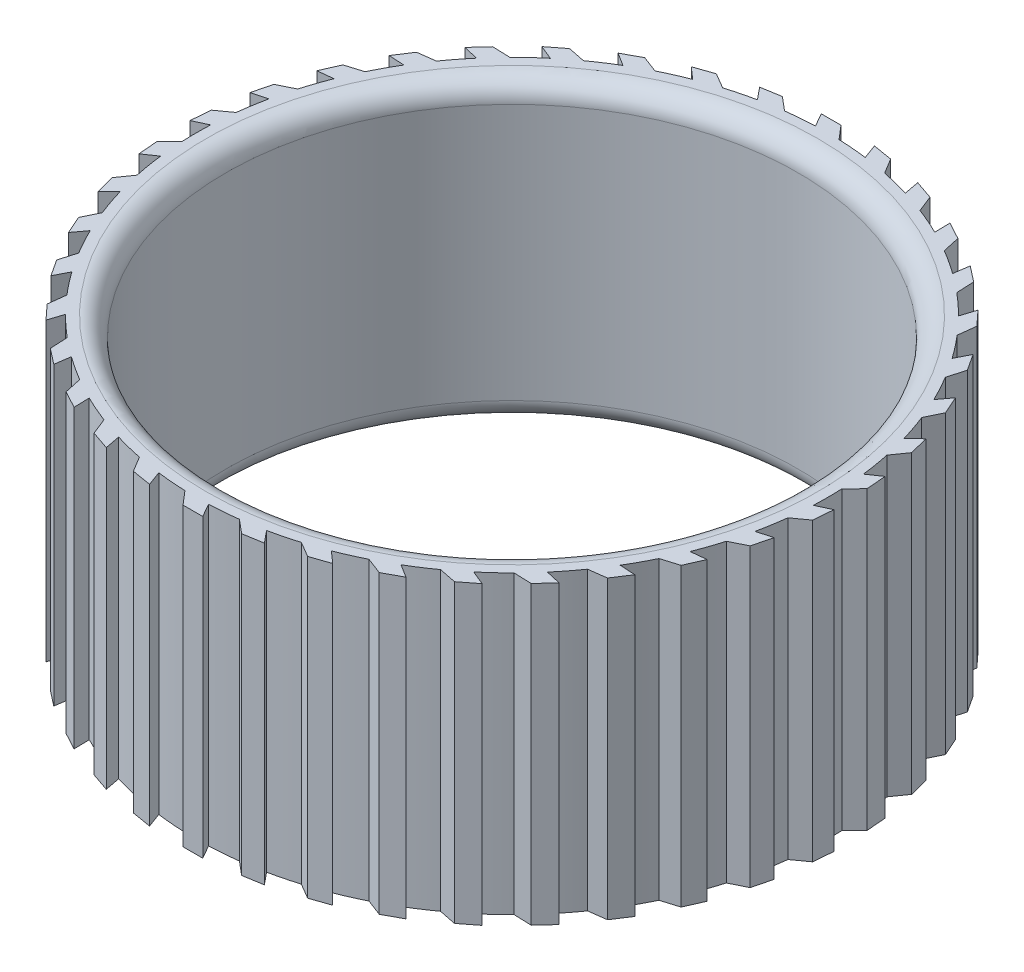
SolidWorks part; units mm, degrees
ref_plane "Front Plane" through (0, 0, 0) normal (0, 0, 1) x (1, 0, 0)
ref_plane "Top Plane" through (0, 0, 0) normal (0, 1, 0) x (1, 0, 0)
ref_plane "Right Plane" through (0, 0, 0) normal (1, 0, 0) x (0, 0, -1)
sketch "Sketch1" plane through (0, 0, 0) normal (0, 1, 0) x (1, 0, 0)
  circle A0 centre (0, 0) radius 29
  circle A1 centre (0, 0) radius 32
  dimension "D1" = 58
  dimension "D2" = 3
extrude "Boss-Extrude1" add sketch "Sketch1" along normal mid plane 30
sketch "Sketch2" plane through (0, -15, 0) normal (0, -1, 0) x (1, 0, 0)
  line L0 (0, -971) -> (0, 49029) construction
  line L1 (0, 33.3457) -> (2, 33.3457)
  line L2 (0, 33.3457) -> (-1.1725, 31.9785)
  line L3 (2, 33.3457) -> (1.2174, 31.9768)
  line L4 (5.4885, 32.8909) -> (4.107, 31.7354)
  line L5 (5.4885, 32.8909) -> (7.4612, 32.5617)
  line L6 (7.4612, 32.5617) -> (6.464, 31.3403)
  line L7 (10.8273, 31.5389) -> (9.2744, 30.6265)
  line L8 (10.8273, 31.5389) -> (12.719, 30.8895)
  line L9 (12.719, 30.8895) -> (11.5343, 29.849)
  line L10 (15.8708, 29.3266) -> (14.1889, 28.6823)
  line L11 (15.8708, 29.3266) -> (17.6297, 28.3747)
  line L12 (17.6297, 28.3747) -> (16.2899, 27.5434)
  line L13 (20.4813, 26.3144) -> (18.7163, 25.9557)
  line L14 (20.4813, 26.3144) -> (22.0596, 25.086)
  line L15 (22.0596, 25.086) -> (20.6012, 24.4865)
  line L16 (24.5332, 22.5844) -> (22.7332, 22.5211)
  line L17 (24.5332, 22.5844) -> (25.8878, 21.1129)
  line L18 (25.8878, 21.1129) -> (24.3506, 20.7617)
  line L19 (27.9159, 18.2383) -> (26.13, 18.4722)
  line L20 (27.9159, 18.2383) -> (29.0098, 16.564)
  line L21 (29.0098, 16.564) -> (27.4358, 16.4705)
  line L22 (30.5371, 13.3948) -> (28.8141, 13.9194)
  line L23 (30.5371, 13.3948) -> (31.3405, 11.5633)
  line L24 (31.3405, 11.5633) -> (29.7725, 11.7301)
  line L25 (32.3253, 8.1859) -> (30.7121, 8.9869)
  line L26 (32.3253, 8.1859) -> (32.8163, 6.2471)
  line L27 (32.8163, 6.2471) -> (31.2972, 6.6697)
  line L28 (33.2318, 2.7537) -> (31.7725, 3.8093)
  line L29 (33.2318, 2.7537) -> (33.3969, 0.7605)
  line L30 (33.3969, 0.7605) -> (31.9681, 1.4274)
  line L31 (33.2318, -2.7537) -> (31.9661, -1.4722)
  line L32 (33.2318, -2.7537) -> (33.0666, -4.7468)
  line L33 (33.0666, -4.7468) -> (31.7671, -3.8538)
  line L34 (32.3253, -8.1859) -> (31.2878, -6.7136)
  line L35 (32.3253, -8.1859) -> (31.8343, -10.1247)
  line L36 (31.8343, -10.1247) -> (30.6995, -9.03)
  line L37 (30.5371, -13.3948) -> (29.7561, -11.7719)
  line L38 (30.5371, -13.3948) -> (29.7337, -15.2263)
  line L39 (29.7337, -15.2263) -> (28.7945, -13.9598)
  line L40 (27.9159, -18.2383) -> (27.4126, -16.509)
  line L41 (27.9159, -18.2383) -> (26.822, -19.9127)
  line L42 (26.822, -19.9127) -> (26.1041, -18.5088)
  line L43 (24.5332, -22.5844) -> (24.3215, -20.7958)
  line L44 (24.5332, -22.5844) -> (23.1786, -24.0558)
  line L45 (23.1786, -24.0558) -> (22.7016, -22.553)
  line L46 (20.4813, -26.3144) -> (20.5669, -24.5154)
  line L47 (20.4813, -26.3144) -> (18.903, -27.5428)
  line L48 (18.903, -27.5428) -> (18.6799, -25.9819)
  line L49 (15.8708, -29.3266) -> (16.2513, -27.5662)
  line L50 (15.8708, -29.3266) -> (14.1118, -30.2785)
  line L51 (14.1118, -30.2785) -> (14.1487, -28.7022)
  line L52 (10.8273, -31.5389) -> (11.4924, -29.8651)
  line L53 (10.8273, -31.5389) -> (8.9357, -32.1883)
  line L54 (8.9357, -32.1883) -> (9.2315, -30.6395)
  line L55 (5.4885, -32.8909) -> (6.42, -31.3494)
  line L56 (5.4885, -32.8909) -> (3.5158, -33.2201)
  line L57 (3.5158, -33.2201) -> (4.0625, -31.7411)
  line L58 (0, -33.3457) -> (1.1725, -31.9785)
  line L59 (0, -33.3457) -> (-2, -33.3457)
  line L60 (-2, -33.3457) -> (-1.2174, -31.9768)
  line L61 (-5.4885, -32.8909) -> (-4.107, -31.7354)
  line L62 (-5.4885, -32.8909) -> (-7.4612, -32.5617)
  line L63 (-7.4612, -32.5617) -> (-6.464, -31.3403)
  line L64 (-10.8273, -31.5389) -> (-9.2744, -30.6265)
  line L65 (-10.8273, -31.5389) -> (-12.719, -30.8895)
  line L66 (-12.719, -30.8895) -> (-11.5343, -29.849)
  line L67 (-15.8708, -29.3266) -> (-14.1889, -28.6823)
  line L68 (-15.8708, -29.3266) -> (-17.6297, -28.3747)
  line L69 (-17.6297, -28.3747) -> (-16.2899, -27.5434)
  line L70 (-20.4813, -26.3144) -> (-18.7163, -25.9557)
  line L71 (-20.4813, -26.3144) -> (-22.0596, -25.086)
  line L72 (-22.0596, -25.086) -> (-20.6012, -24.4865)
  line L73 (-24.5332, -22.5844) -> (-22.7332, -22.5211)
  line L74 (-24.5332, -22.5844) -> (-25.8878, -21.1129)
  line L75 (-25.8878, -21.1129) -> (-24.3506, -20.7617)
  line L76 (-27.9159, -18.2383) -> (-26.13, -18.4722)
  line L77 (-27.9159, -18.2383) -> (-29.0098, -16.564)
  line L78 (-29.0098, -16.564) -> (-27.4358, -16.4705)
  line L79 (-30.5371, -13.3948) -> (-28.8141, -13.9194)
  line L80 (-30.5371, -13.3948) -> (-31.3405, -11.5633)
  line L81 (-31.3405, -11.5633) -> (-29.7725, -11.7301)
  line L82 (-32.3253, -8.1859) -> (-30.7121, -8.9869)
  line L83 (-32.3253, -8.1859) -> (-32.8163, -6.2471)
  line L84 (-32.8163, -6.2471) -> (-31.2972, -6.6697)
  line L85 (-33.2318, -2.7537) -> (-31.7725, -3.8093)
  line L86 (-33.2318, -2.7537) -> (-33.3969, -0.7605)
  line L87 (-33.3969, -0.7605) -> (-31.9681, -1.4274)
  line L88 (-33.2318, 2.7537) -> (-31.9661, 1.4722)
  line L89 (-33.2318, 2.7537) -> (-33.0666, 4.7468)
  line L90 (-33.0666, 4.7468) -> (-31.7671, 3.8538)
  line L91 (-32.3253, 8.1859) -> (-31.2878, 6.7136)
  line L92 (-32.3253, 8.1859) -> (-31.8343, 10.1247)
  line L93 (-31.8343, 10.1247) -> (-30.6995, 9.03)
  line L94 (-30.5371, 13.3948) -> (-29.7561, 11.7719)
  line L95 (-30.5371, 13.3948) -> (-29.7337, 15.2263)
  line L96 (-29.7337, 15.2263) -> (-28.7945, 13.9598)
  line L97 (-27.9159, 18.2383) -> (-27.4126, 16.509)
  line L98 (-27.9159, 18.2383) -> (-26.822, 19.9127)
  line L99 (-26.822, 19.9127) -> (-26.1041, 18.5088)
  line L100 (-24.5332, 22.5844) -> (-24.3215, 20.7958)
  line L101 (-24.5332, 22.5844) -> (-23.1786, 24.0558)
  line L102 (-23.1786, 24.0558) -> (-22.7016, 22.553)
  line L103 (-20.4813, 26.3144) -> (-20.5669, 24.5154)
  line L104 (-20.4813, 26.3144) -> (-18.903, 27.5428)
  line L105 (-18.903, 27.5428) -> (-18.6799, 25.9819)
  line L106 (-15.8708, 29.3266) -> (-16.2513, 27.5662)
  line L107 (-15.8708, 29.3266) -> (-14.1118, 30.2785)
  line L108 (-14.1118, 30.2785) -> (-14.1487, 28.7022)
  line L109 (-10.8273, 31.5389) -> (-11.4924, 29.8651)
  line L110 (-10.8273, 31.5389) -> (-8.9357, 32.1883)
  line L111 (-8.9357, 32.1883) -> (-9.2315, 30.6395)
  line L112 (-5.4885, 32.8909) -> (-6.42, 31.3494)
  line L113 (-5.4885, 32.8909) -> (-3.5158, 33.2201)
  line L114 (-3.5158, 33.2201) -> (-4.0625, 31.7411)
  arc A0 (1.2174, 31.9768) -> (-1.1725, 31.9785) centre (0, 0) ccw
  circle A1 centre (0, 0) radius 32 construction
  arc A2 (6.464, 31.3403) -> (4.107, 31.7354) centre (0, 0) ccw
  arc A3 (11.5343, 29.849) -> (9.2744, 30.6265) centre (0, 0) ccw
  arc A4 (16.2899, 27.5434) -> (14.1889, 28.6823) centre (0, 0) ccw
  arc A5 (20.6012, 24.4865) -> (18.7163, 25.9557) centre (0, 0) ccw
  arc A6 (24.3506, 20.7617) -> (22.7332, 22.5211) centre (0, 0) ccw
  arc A7 (27.4358, 16.4705) -> (26.13, 18.4722) centre (0, 0) ccw
  arc A8 (29.7725, 11.7301) -> (28.8141, 13.9194) centre (0, 0) ccw
  arc A9 (31.2972, 6.6697) -> (30.7121, 8.9869) centre (0, 0) ccw
  arc A10 (31.9681, 1.4274) -> (31.7725, 3.8093) centre (0, 0) ccw
  arc A11 (31.7671, -3.8538) -> (31.9661, -1.4722) centre (0, 0) ccw
  arc A12 (30.6995, -9.03) -> (31.2878, -6.7136) centre (0, 0) ccw
  arc A13 (28.7945, -13.9598) -> (29.7561, -11.7719) centre (0, 0) ccw
  arc A14 (26.1041, -18.5088) -> (27.4126, -16.509) centre (0, 0) ccw
  arc A15 (22.7016, -22.553) -> (24.3215, -20.7958) centre (0, 0) ccw
  arc A16 (18.6799, -25.9819) -> (20.5669, -24.5154) centre (0, 0) ccw
  arc A17 (14.1487, -28.7022) -> (16.2513, -27.5662) centre (0, 0) ccw
  arc A18 (9.2315, -30.6395) -> (11.4924, -29.8651) centre (0, 0) ccw
  arc A19 (4.0625, -31.7411) -> (6.42, -31.3494) centre (0, 0) ccw
  arc A20 (-1.2174, -31.9768) -> (1.1725, -31.9785) centre (0, 0) ccw
  arc A21 (-6.464, -31.3403) -> (-4.107, -31.7354) centre (0, 0) ccw
  arc A22 (-11.5343, -29.849) -> (-9.2744, -30.6265) centre (0, 0) ccw
  arc A23 (-16.2899, -27.5434) -> (-14.1889, -28.6823) centre (0, 0) ccw
  arc A24 (-20.6012, -24.4865) -> (-18.7163, -25.9557) centre (0, 0) ccw
  arc A25 (-24.3506, -20.7617) -> (-22.7332, -22.5211) centre (0, 0) ccw
  arc A26 (-27.4358, -16.4705) -> (-26.13, -18.4722) centre (0, 0) ccw
  arc A27 (-29.7725, -11.7301) -> (-28.8141, -13.9194) centre (0, 0) ccw
  arc A28 (-31.2972, -6.6697) -> (-30.7121, -8.9869) centre (0, 0) ccw
  arc A29 (-31.9681, -1.4274) -> (-31.7725, -3.8093) centre (0, 0) ccw
  arc A30 (-31.7671, 3.8538) -> (-31.9661, 1.4722) centre (0, 0) ccw
  arc A31 (-30.6995, 9.03) -> (-31.2878, 6.7136) centre (0, 0) ccw
  arc A32 (-28.7945, 13.9598) -> (-29.7561, 11.7719) centre (0, 0) ccw
  arc A33 (-26.1041, 18.5088) -> (-27.4126, 16.509) centre (0, 0) ccw
  arc A34 (-22.7016, 22.553) -> (-24.3215, 20.7958) centre (0, 0) ccw
  arc A35 (-18.6799, 25.9819) -> (-20.5669, 24.5154) centre (0, 0) ccw
  arc A36 (-14.1487, 28.7022) -> (-16.2513, 27.5662) centre (0, 0) ccw
  arc A37 (-9.2315, 30.6395) -> (-11.4924, 29.8651) centre (0, 0) ccw
  arc A38 (-4.0625, 31.7411) -> (-6.42, 31.3494) centre (0, 0) ccw
  point P159 (0, 0)
  dimension "D1" = 2
  dimension "D2" = 1.1725
  dimension "D3" = 1.2174
  dimension "D4" = 38
extrude "Boss-Extrude2" add sketch "Sketch2" against normal blind 30
fillet "Fillet1" radius 2 2 edges at (0, 15, 29) (0, -15, 29)
